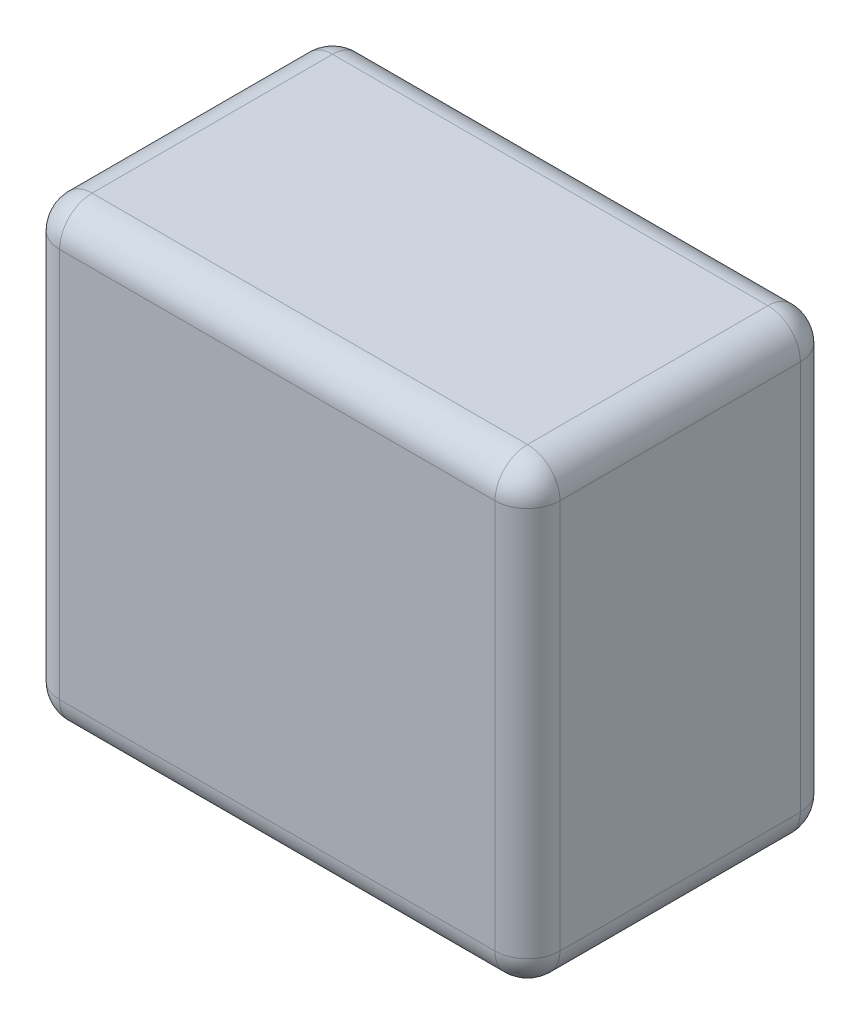
SolidWorks part; units mm, degrees
ref_plane "Alzado" through (0, 0, 0) normal (0, 0, 1) x (1, 0, 0)
ref_plane "Planta" through (0, 0, 0) normal (0, 1, 0) x (1, 0, 0)
ref_plane "Vista lateral" through (0, 0, 0) normal (1, 0, 0) x (0, 0, -1)
sketch "Croquis1" plane through (0, 0, 0) normal (0, 0, 1) x (1, 0, 0)
  line L1 (0, 0) -> (77, 0)
  line L2 (0, 0) -> (0, 70)
  line L3 (0, 70) -> (77, 70)
  line L4 (77, 0) -> (77, 70)
  dimension "D1" = 77
  dimension "D2" = 70
extrude "Saliente-Extruir1" add sketch "Croquis1" along normal blind 47
fillet "Redondeo1" radius 5 12 edges at (0, 35, 0) (0, 70, 23.5) (38.5, 70, 0) (38.5, 70, 47) (0, 35, 47) (77, 35, 47) (77, 70, 23.5) (77, 35, 0) (0, 0, 23.5) (38.5, 0, 47) (77, 0, 23.5) (38.5, 0, 0)
